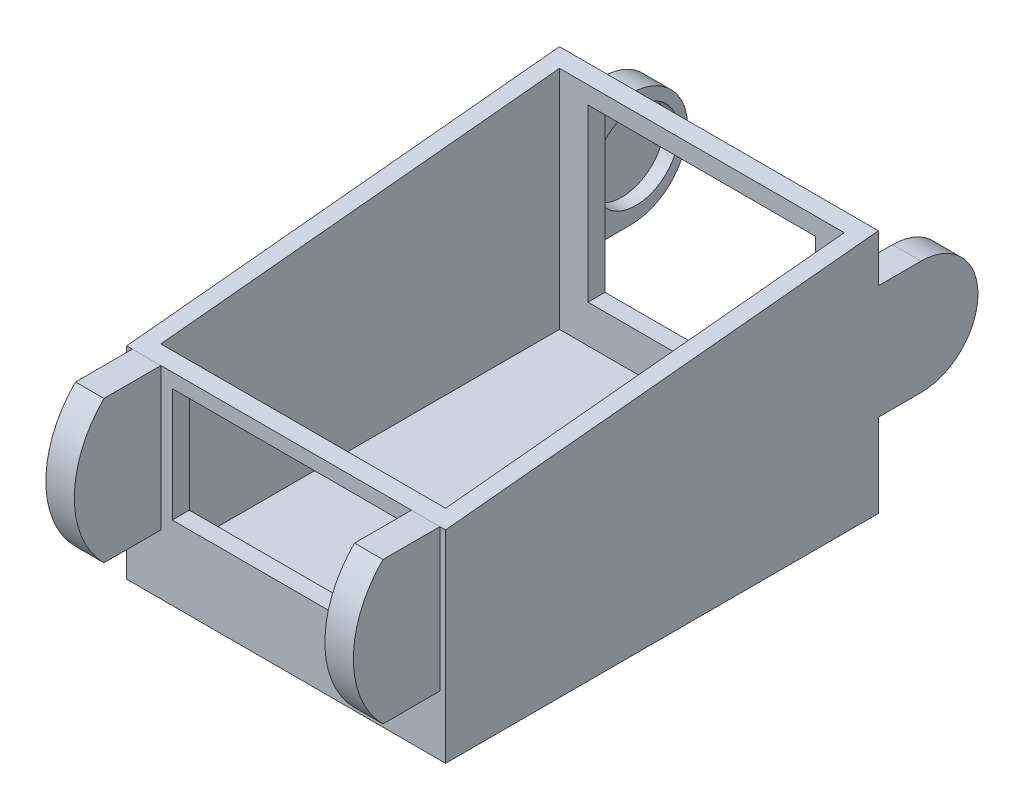
SolidWorks part; units mm, degrees
ref_plane "Front Plane" through (0, 0, 0) normal (0, 0, 1) x (1, 0, 0)
ref_plane "Top Plane" through (0, 0, 0) normal (0, 1, 0) x (1, 0, 0)
ref_plane "Right Plane" through (0, 0, 0) normal (1, 0, 0) x (0, 0, -1)
sketch "Sketch1" plane through (0, 0, 0) normal (0, 1, 0) x (1, 0, 0)
  line L1 (25, -35) -> (-25, -35)
  line L2 (25, -35) -> (25, 35)
  line L3 (25, 35) -> (-25, 35)
  line L4 (-25, -35) -> (-25, 35)
  line L5 (25, -35) -> (-25, 35) construction
  line L6 (25, 35) -> (-25, -35) construction
  point P0 (0, 0)
extrude "Boss-Extrude1" add sketch "Sketch1" along normal blind 40
shell "Shell1" thickness 3
ref_plane "Plane1" through (25, 0, 0) normal (-1, 0, 0) x (0, 0, 1)
sketch "Sketch2" plane through (25, 0, 0) normal (-1, 0, 0) x (0, 0, 1)
  line L0 (38, 32.5) -> (48, 32.5)
  line L1 (38, 40) -> (38, -3) construction
  line L3 (48, 7.5) -> (38, 7.5)
  line L6 (38, 32.5) -> (38, 7.5)
  arc A0 (48, 32.5) -> (48, 7.5) centre (35.576, 20) cw
  dimension "D1" = 7.5
  dimension "D2" = 25
  dimension "D4" = 10
extrude "Boss-Extrude2" add sketch "Sketch2" along normal blind 3 and the other way blind 2
ref_plane "Plane2" through (0, 0, 0) normal (-1, 0, 0) x (0, 0, 1)
mirror "Mirror1" about plane through (0, 0, 0) normal (-1, 0, 0) of "Boss-Extrude2"
ref_plane "Plane9" through (-28, 0, 0) normal (-1, 0, 0) x (0, 0, 1)
sketch "Sketch4" plane through (-28, 0, 0) normal (-1, 0, 0) x (0, 0, 1)
  line L0 (-38, 40) -> (38, 40)
  line L1 (38, 40) -> (38, 32.5)
  line L2 (38, 32.5) -> (-38, 40)
extrude "Cut-Extrude1" cut sketch "Sketch4" against normal through all contours L2 L0 L1
sketch "Sketch7" plane through (-28, 0, 0) normal (-1, 0, 0) x (0, 0, 1)
  line L0 (-38, 31.636) -> (-45.5, 31.636)
  line L1 (-38, 40) -> (-38, -3) construction
  line L3 (-45.5, 11.636) -> (-38, 11.636)
  line L8 (-38, 31.636) -> (-38, 11.636)
  arc A0 (-45.5, 31.636) -> (-45.5, 11.636) centre (-45.5, 21.636) ccw
  dimension "D1" = 7.5
extrude "Boss-Extrude4" add sketch "Sketch7" against normal blind 5 contours L3 L8 L0 A0
mirror "Mirror3" about plane through (0, 0, 0) normal (-1, 0, 0) of "Boss-Extrude4"
ref_plane "Plane17" through (23, 0, 0) normal (-1, 0, 0) x (0, 0, 1)
sketch "Sketch8" plane through (23, 0, 0) normal (-1, 0, 0) x (0, 0, 1)
  line L0 (-45.5, 11.636) -> (-38, 11.636) construction
  line L1 (-38, 31.636) -> (-38, 11.636) construction
  line L2 (-38, 31.636) -> (-45.5, 31.636) construction
  line L3 (-45.5, 11.636) -> (-38, 11.636)
  line L4 (-38, 31.636) -> (-38, 11.636)
  line L5 (-38, 31.636) -> (-45.5, 31.636)
  line L6 (-63, 21.636) -> (-38, 21.636) construction
  circle A2 centre (-46.4559, 21.636) radius 7.5
extrude "Cut-Extrude2" cut sketch "Sketch8" against normal blind 2.5 contours A2
mirror "Mirror4" about plane through (0, 0, 0) normal (-1, 0, 0) of "Cut-Extrude2"
ref_plane "Plane18" through (0, 0, -38) normal (0, 0, -1) x (-1, 0, 0)
sketch "Sketch9" plane through (0, 0, -38) normal (0, 0, -1) x (-1, 0, 0)
  line L5 (20, 6.636) -> (-20, 6.636)
  line L7 (20, 6.636) -> (20, 36.636)
  line L8 (20, 36.636) -> (-20, 36.636)
  line L9 (-20, 6.636) -> (-20, 36.636)
  line L10 (-23, 21.636) -> (23, 21.636) construction
  line L11 (20, 6.636) -> (-20, 36.636) construction
  line L12 (20, 36.636) -> (-20, 6.636) construction
  point P0 (0, 21.636)
extrude "Cut-Extrude3" cut sketch "Sketch9" against normal blind 10 contours L5 L9 L8 L7
ref_plane "Plane21" through (0, 0, 38) normal (0, 0, 1) x (1, 0, 0)
sketch3d "3DSketch1"
  line L3 (20, 10, 38) -> (-20, 10, 38)
  line L4 (-20, 20, 38) -> (20, 20, 38) construction
  line L5 (20, 10, 38) -> (20, 30, 38)
  line L6 (20, 30, 38) -> (-20, 30, 38)
  line L7 (-20, 10, 38) -> (-20, 30, 38)
  line L8 (20, 10, 38) -> (-20, 30, 38) construction
  line L9 (20, 30, 38) -> (-20, 10, 38) construction
  point P0 (0, 20, 38)
extrude "Cut-Extrude4" cut sketch "3DSketch1" along direction (0, 0, -1) on the side against the normal blind 10
